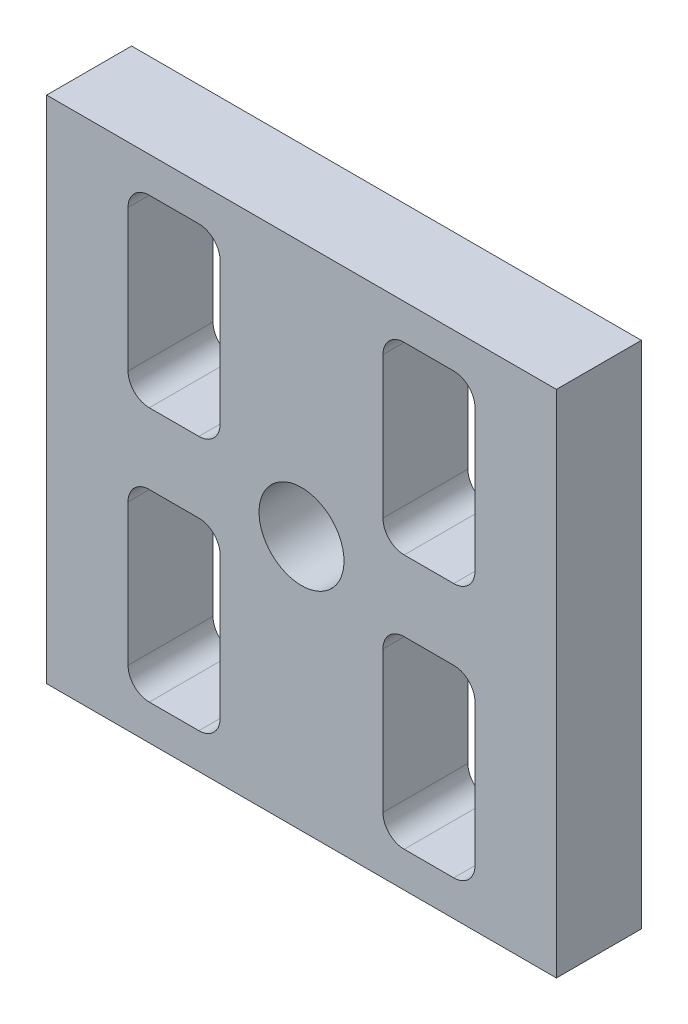
SolidWorks part; units mm, degrees
ref_plane "Alzado" through (0, 0, 0) normal (0, 0, 1) x (1, 0, 0)
ref_plane "Planta" through (0, 0, 0) normal (0, 1, 0) x (1, 0, 0)
ref_plane "Vista lateral" through (0, 0, 0) normal (1, 0, 0) x (0, 0, -1)
sketch "Model" plane through (0, 0, 0) normal (0, 0, 1) x (1, 0, 0)
  line L0 (208.8359, 161.3332) -> (208.8359, 179.3332)
  line L1 (190.8359, 179.3332) -> (190.8359, 161.3332)
  line L2 (202.7109, 172.3332) -> (202.7109, 177.3332)
  line L3 (203.4609, 178.0832) -> (205.2109, 178.0832)
  line L4 (205.9609, 177.3332) -> (205.9609, 172.3332)
  line L5 (205.2109, 171.5832) -> (203.4609, 171.5832)
  line L6 (205.9609, 168.3332) -> (205.9609, 163.3332)
  line L7 (205.2109, 162.5832) -> (203.4609, 162.5832)
  line L8 (202.7109, 163.3332) -> (202.7109, 168.3332)
  line L9 (203.4609, 169.0832) -> (205.2109, 169.0832)
  line L10 (196.9609, 168.3332) -> (196.9609, 163.3332)
  line L11 (196.2109, 162.5832) -> (194.4609, 162.5832)
  line L12 (193.7109, 163.3332) -> (193.7109, 168.3332)
  line L13 (194.4609, 169.0832) -> (196.2109, 169.0832)
  line L14 (196.9609, 177.3332) -> (196.9609, 172.3332)
  line L15 (196.2109, 171.5832) -> (194.4609, 171.5832)
  line L16 (193.7109, 172.3332) -> (193.7109, 177.3332)
  line L17 (194.4609, 178.0832) -> (196.2109, 178.0832)
  line L18 (190.8359, 179.3332) -> (208.8359, 179.3332)
  line L19 (190.8359, 161.3332) -> (208.8359, 161.3332)
  arc A0 (203.4609, 178.0832) -> (202.7109, 177.3332) centre (203.4609, 177.3332) ccw
  arc A1 (205.9609, 177.3332) -> (205.2109, 178.0832) centre (205.2109, 177.3332) ccw
  arc A2 (205.2109, 171.5832) -> (205.9609, 172.3332) centre (205.2109, 172.3332) ccw
  arc A3 (202.7109, 172.3332) -> (203.4609, 171.5832) centre (203.4609, 172.3332) ccw
  arc A4 (205.2109, 162.5832) -> (205.9609, 163.3332) centre (205.2109, 163.3332) ccw
  arc A5 (202.7109, 163.3332) -> (203.4609, 162.5832) centre (203.4609, 163.3332) ccw
  arc A6 (203.4609, 169.0832) -> (202.7109, 168.3332) centre (203.4609, 168.3332) ccw
  arc A7 (205.9609, 168.3332) -> (205.2109, 169.0832) centre (205.2109, 168.3332) ccw
  arc A8 (196.2109, 162.5832) -> (196.9609, 163.3332) centre (196.2109, 163.3332) ccw
  arc A9 (193.7109, 163.3332) -> (194.4609, 162.5832) centre (194.4609, 163.3332) ccw
  arc A10 (194.4609, 169.0832) -> (193.7109, 168.3332) centre (194.4609, 168.3332) ccw
  arc A11 (196.9609, 168.3332) -> (196.2109, 169.0832) centre (196.2109, 168.3332) ccw
  arc A12 (196.2109, 171.5832) -> (196.9609, 172.3332) centre (196.2109, 172.3332) ccw
  arc A13 (193.7109, 172.3332) -> (194.4609, 171.5832) centre (194.4609, 172.3332) ccw
  arc A14 (194.4609, 178.0832) -> (193.7109, 177.3332) centre (194.4609, 177.3332) ccw
  arc A15 (196.9609, 177.3332) -> (196.2109, 178.0832) centre (196.2109, 177.3332) ccw
  circle A16 centre (199.8359, 170.3332) radius 1.5
extrude "Saliente-Extruir1" add sketch "Model" along normal blind 3
